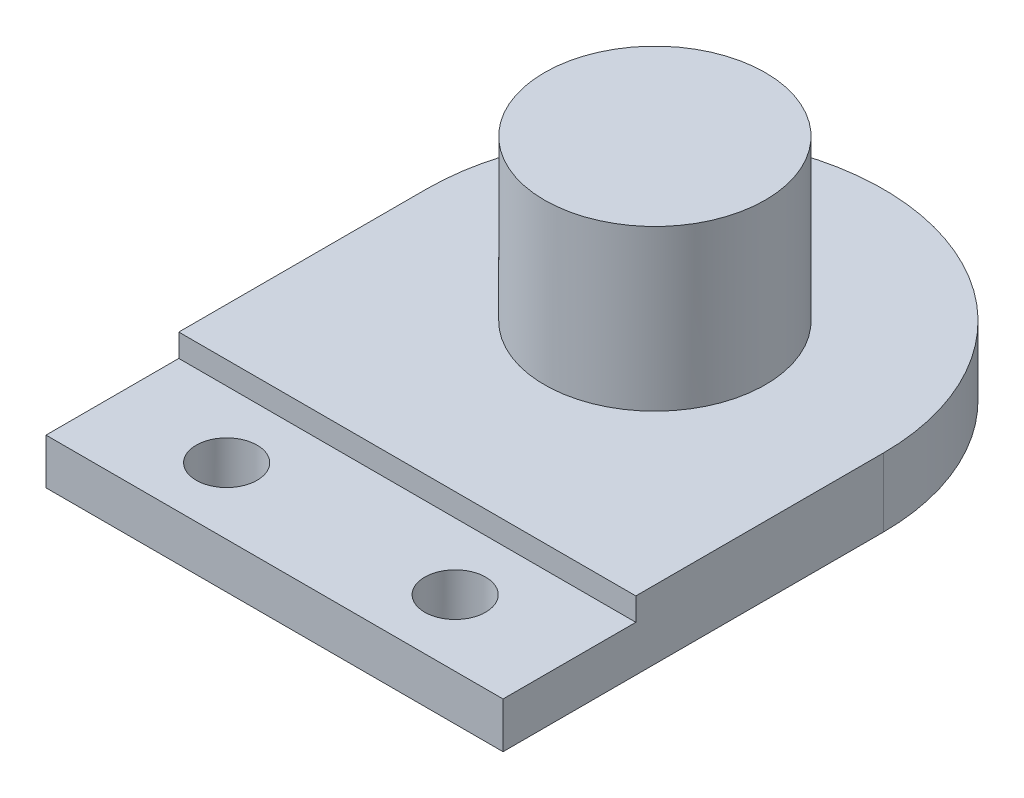
SolidWorks part; units mm, degrees
ref_plane "Front Plane" through (0, 0, 0) normal (0, 0, 1) x (1, 0, 0)
ref_plane "Top Plane" through (0, 0, 0) normal (0, 1, 0) x (1, 0, 0)
ref_plane "Right Plane" through (0, 0, 0) normal (1, 0, 0) x (0, 0, -1)
sketch "Sketch2" plane through (0, 0, 0) normal (0, 1, 0) x (1, 0, 0)
  line L0 (0, 0) -> (0, 9.9863)
  line L1 (0, 0) -> (12, 0)
  line L2 (12, 0) -> (12, 9.9863)
  arc A0 (0, 9.9863) -> (12, 9.9863) centre (6, 9.9863) cw
  dimension "D1" = 9.9863
  dimension "D2" = 12
extrude "Boss-Extrude1" add sketch "Sketch2" along normal blind 1.8
sketch "Sketch3" plane through (0, 1.8, 0) normal (0, 1, 0) x (1, 0, 0)
  line L0 (0, 0) -> (0, 3.4863)
  line L1 (0, 9.9863) -> (0, 0) construction
  line L2 (0, 3.4863) -> (12, 3.4863)
  line L3 (12, 0) -> (12, 9.9863) construction
  line L4 (12, 3.4863) -> (12, 0)
  line L5 (12, 0) -> (0, 0)
  dimension "D1" = 3.4863
extrude "Cut-Extrude1" cut sketch "Sketch3" against normal blind 0.6
sketch "Sketch4" plane through (0, 1.8, 0) normal (0, 1, 0) x (1, 0, 0)
  circle A0 centre (6, 9.9863) radius 2.9
  dimension "D1" = 5.8
extrude "Boss-Extrude2" add sketch "Sketch4" along normal blind 4.2
sketch "Sketch5" plane through (0, 1.2, 0) normal (0, 1, 0) x (1, 0, 0)
  line L0 (0, 1.7431) -> (12, 1.7431) construction
  line L1 (0, 3.4863) -> (0, 0) construction
  line L2 (12, 0) -> (12, 3.4863) construction
  circle A0 centre (3, 1.7431) radius 0.8
  circle A1 centre (9, 1.7431) radius 0.8
  point P10 (0, 0)
  point P11 (6, 1.7431)
  dimension "D1" = 1.6
  dimension "D2" = 6
  dimension "D3" = 3
  dimension "D4" = 3
extrude "Cut-Extrude2" cut sketch "Sketch5" against normal up to next
